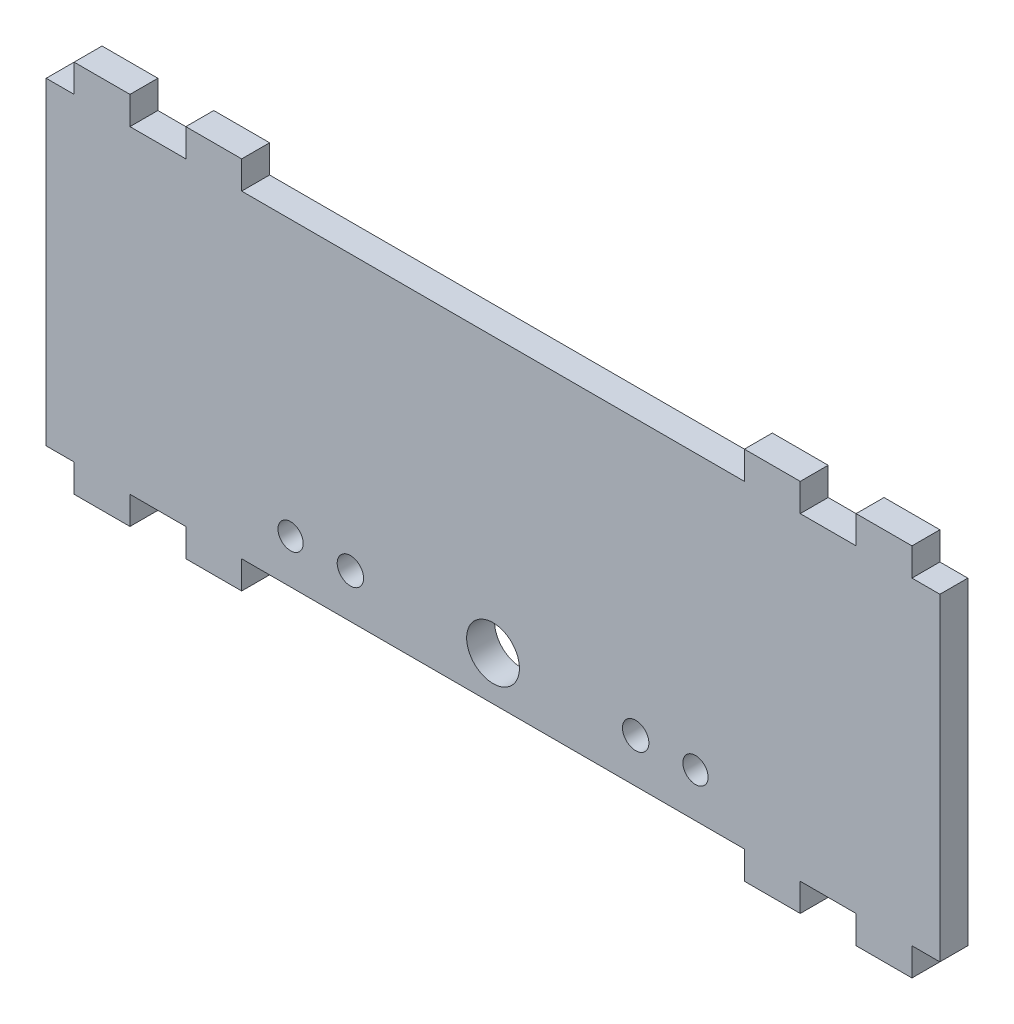
SolidWorks part; units mm, degrees
material "Acrylic (Medium-high impact)"
ref_plane "Front Plane" through (0, 0, 0) normal (0, 0, 1) x (1, 0, 0)
ref_plane "Top Plane" through (0, 0, 0) normal (0, 1, 0) x (1, 0, 0)
ref_plane "Right Plane" through (0, 0, 0) normal (1, 0, 0) x (0, 0, -1)
sketch "Sketch1" plane through (0, 0, 0) normal (0, 0, 1) x (1, 0, 0)
  line L0 (3.175, 0) -> (3.175, -3.175)
  line L1 (0, 0) -> (3.175, 0)
  line L2 (0, 0) -> (0, 36.195)
  line L3 (0, 36.195) -> (3.175, 36.195)
  line L4 (101.6, 0) -> (101.6, 36.195)
  line L5 (3.175, -3.175) -> (9.525, -3.175)
  line L6 (9.525, -3.175) -> (9.525, 0)
  line L7 (15.875, 0) -> (15.875, -3.175)
  line L8 (15.875, -3.175) -> (22.225, -3.175)
  line L9 (22.225, -3.175) -> (22.225, 0)
  line L10 (50.8, 36.195) -> (50.8, 0) construction
  line L11 (79.375, -3.175) -> (79.375, 0)
  line L12 (85.725, -3.175) -> (79.375, -3.175)
  line L13 (85.725, 0) -> (85.725, -3.175)
  line L14 (92.075, -3.175) -> (92.075, 0)
  line L15 (98.425, -3.175) -> (92.075, -3.175)
  line L16 (98.425, 0) -> (98.425, -3.175)
  line L17 (9.525, 0) -> (15.875, 0)
  line L18 (22.225, 0) -> (79.375, 0)
  line L19 (85.725, 0) -> (92.075, 0)
  line L20 (98.425, 0) -> (101.6, 0)
  line L21 (0, 18.0975) -> (101.6, 18.0975) construction
  line L22 (98.425, 36.195) -> (98.425, 39.37)
  line L23 (98.425, 39.37) -> (92.075, 39.37)
  line L24 (92.075, 39.37) -> (92.075, 36.195)
  line L25 (85.725, 36.195) -> (85.725, 39.37)
  line L26 (85.725, 39.37) -> (79.375, 39.37)
  line L27 (79.375, 39.37) -> (79.375, 36.195)
  line L28 (22.225, 39.37) -> (22.225, 36.195)
  line L29 (15.875, 39.37) -> (22.225, 39.37)
  line L30 (15.875, 36.195) -> (15.875, 39.37)
  line L31 (9.525, 39.37) -> (9.525, 36.195)
  line L32 (3.175, 39.37) -> (9.525, 39.37)
  line L33 (3.175, 36.195) -> (3.175, 39.37)
  line L34 (9.525, 36.195) -> (15.875, 36.195)
  line L35 (22.225, 36.195) -> (79.375, 36.195)
  line L36 (85.725, 36.195) -> (92.075, 36.195)
  line L37 (98.425, 36.195) -> (101.6, 36.195)
  circle A0 centre (34.585, 5) radius 1.5
  circle A1 centre (27.7875, 5) radius 1.435
  circle A2 centre (67.015, 5) radius 1.5
  circle A3 centre (73.8125, 5) radius 1.435
  circle A4 centre (50.8, 5) radius 3
  dimension "D8" = 3
  dimension "D9" = 2.87
  dimension "D12" = 6
  dimension "D1" = 101.6
  dimension "D2" = 36.195
  dimension "D3" = 6.35
  dimension "D4" = 3.175
  dimension "D5" = 6.35
  dimension "D6" = 28.575
  dimension "D7" = 5
  dimension "D10" = 16.215
  dimension "D11" = 23.0125
  dimension "D13" = 3.175
extrude "Boss-Extrude1" add sketch "Sketch1" along normal blind 3.175
